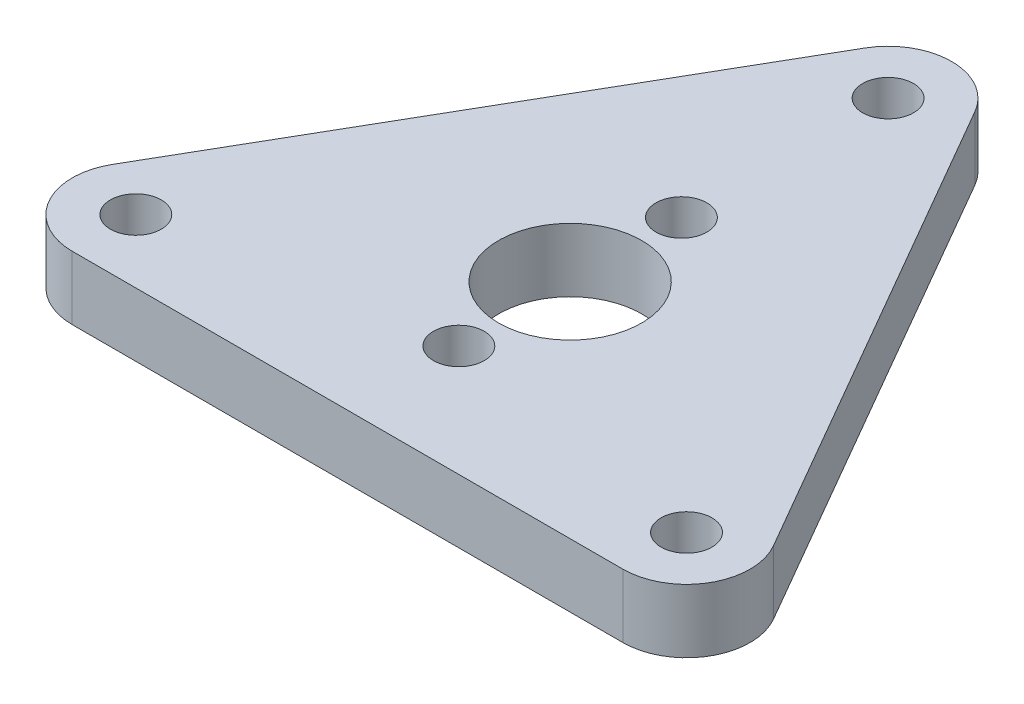
SolidWorks part; units mm, degrees
ref_plane "前视基准面" through (0, 0, 0) normal (0, 0, 1) x (1, 0, 0)
ref_plane "上视基准面" through (0, 0, 0) normal (0, 1, 0) x (1, 0, 0)
ref_plane "右视基准面" through (0, 0, 0) normal (1, 0, 0) x (0, 0, -1)
sketch "草图2" plane through (0, 0, 0) normal (0, 1, 0) x (1, 0, 0)
  line L0 (0, -7) -> (0, 7) construction
  line L1 (-3.4641, 22) -> (-20.7846, -8)
  line L2 (-17.3205, -14) -> (17.3205, -14)
  line L3 (20.7846, -8) -> (3.4641, 22)
  circle A0 centre (0, 0) radius 14 construction
  circle A1 centre (0, 7) radius 1.6
  circle A2 centre (0, -7) radius 1.6
  circle A3 centre (0, 0) radius 20 construction
  circle A4 centre (0, 20) radius 1.6
  circle A5 centre (17.3205, -10) radius 1.6
  circle A6 centre (-17.3205, -10) radius 1.6
  arc A7 (17.3205, -14) -> (20.7846, -8) centre (17.3205, -10) ccw
  arc A8 (-20.7846, -8) -> (-17.3205, -14) centre (-17.3205, -10) ccw
  arc A9 (-3.4641, 22) -> (3.4641, 22) centre (0, 20) cw
  circle A10 centre (0, 0) radius 4.5
  point P9 (0, 0)
  point P20 (0, 0)
  dimension "D1" = 3.2
  dimension "D3" = 40
  dimension "D4" = 3.2
  dimension "D5" = 4
  dimension "D7" = 4
  dimension "D8" = 9
  dimension "D2" = 14
  dimension "D6" = 3
extrude "凸台-拉伸1" add sketch "草图2" along normal mid plane 4
